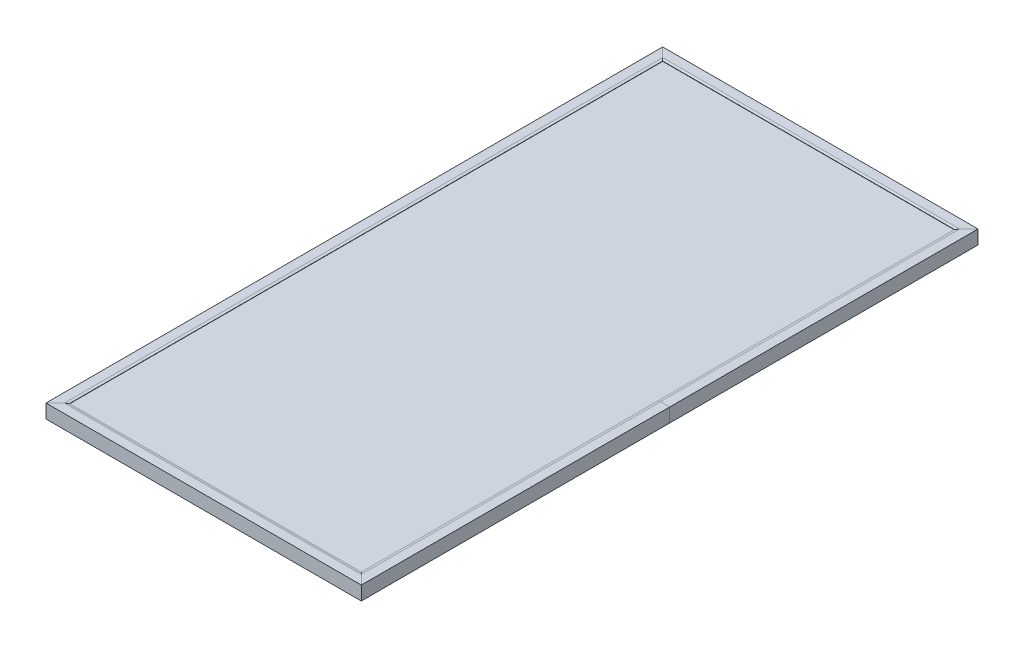
SolidWorks part; units mm, degrees
ref_plane "Front Plane" through (0, 0, 0) normal (0, 0, 1) x (1, 0, 0)
ref_plane "Top Plane" through (0, 0, 0) normal (0, 1, 0) x (1, 0, 0)
ref_plane "Right Plane" through (0, 0, 0) normal (1, 0, 0) x (0, 0, -1)
sketch "Solar Panel Dimensions" plane through (0, 0, 0) normal (0, 1, 0) x (1, 0, 0)
  line L0 (-403.86, 789.94) -> (403.86, 789.94)
  line L1 (-403.86, 789.94) -> (-403.86, -789.94)
  line L2 (403.86, 789.94) -> (403.86, -789.94)
  line L3 (-403.86, -789.94) -> (403.86, -789.94)
  line L4 (-403.86, 789.94) -> (403.86, -789.94) construction
  line L5 (403.86, 789.94) -> (-403.86, -789.94) construction
  point P1 (0, 0)
  dimension "D1" = 1579.88
  dimension "D2" = 807.72
sketch "Bracket" plane through (0, 0, 0) normal (0, 0, 1) x (1, 0, 0)
  line L0 (403.86, 0) -> (373.86, 0)
  line L1 (373.86, 33.56) -> (373.86, 34.2641)
  line L2 (-403.86, 0) -> (403.86, 0) construction
  line L3 (-403.86, 0) -> (403.86, 0) construction
  line L4 (373.86, 0) -> (373.86, 1.2)
  line L5 (373.86, 1.2) -> (399.86, 1.2)
  line L6 (399.86, 1.2) -> (399.86, 33.56)
  line L7 (399.86, 33.56) -> (373.86, 33.56)
  line L8 (373.86, 33.56) -> (373.86, 35.56) construction
  line L9 (373.86, 35.56) -> (403.86, 35.56) construction
  line L10 (403.86, 35.56) -> (403.86, 0)
  line L11 (373.86, 34.2641) -> (380.2941, 35.56)
  line L12 (-403.86, 0) -> (403.86, 0) construction
  line L13 (380.2941, 35.56) -> (403.86, 35.56)
  point P3 (403.86, 0)
  dimension "D1" = 1.2
  dimension "D2" = 2
  dimension "D3" = 4
  dimension "D4" = 35.56
  dimension "D5" = 30
  dimension "D6" = 6.4341
  dimension "D7" = 0.7041
sweep "Sweep1" add profiles "Bracket" path "Solar Panel Dimensions"
sketch "Sketch3" plane through (0, 33.56, 0) normal (0, -1, 0) x (1, 0, 0)
  line L1 (-373.86, 759.94) -> (373.86, 759.94)
  line L2 (-373.86, 759.94) -> (-373.86, -759.94)
  line L3 (-373.86, -759.94) -> (373.86, -759.94)
  line L4 (373.86, 759.94) -> (373.86, -759.94)
extrude "Boss-Extrude1" add sketch "Sketch3" along normal blind 3 separate body
sketch "Sketch4" plane through (0, 30.56, 0) normal (0, -1, 0) x (1, 0, 0)
  line L0 (55, -659.94) -> (-55, -659.94)
  line L1 (-55, -659.94) -> (-55, -584.94)
  line L2 (-55, -584.94) -> (-20, -584.94)
  line L3 (-20, -584.94) -> (-20, -604.94)
  line L4 (-20, -604.94) -> (20, -604.94)
  line L5 (20, -604.94) -> (20, -584.94)
  line L6 (20, -584.94) -> (55, -584.94)
  line L7 (55, -584.94) -> (55, -659.94)
  line L8 (373.86, -759.94) -> (-373.86, -759.94) construction
  line L9 (0, -759.94) -> (0, -659.94) construction
  dimension "D1" = 35
  dimension "D2" = 35
  dimension "D3" = 40
  dimension "D4" = 75
  dimension "D5" = 20
  dimension "D6" = 100
extrude "Boss-Extrude2" add sketch "Sketch4" along normal blind 10
ref_plane "Plane1" through (0, 0, 0) normal (0, -1, 0) x (-1, 0, 0)
sketch "Sketch5" plane through (0, 0, 0) normal (0, -1, 0) x (-1, 0, 0)
  line L0 (-384.36, 651.44) -> (-384.36, 646.44) construction
  line L1 (-379.86, 651.44) -> (-379.86, 646.44)
  line L2 (-388.86, 651.44) -> (-388.86, 646.44)
  line L3 (-403.86, 789.94) -> (-403.86, 0) construction
  line L4 (403.86, 789.94) -> (-403.86, 789.94) construction
  line L5 (-384.36, 401.44) -> (-384.36, 396.44) construction
  line L6 (-379.86, 401.44) -> (-379.86, 396.44)
  line L7 (-388.86, 401.44) -> (-388.86, 396.44)
  line L8 (-384.36, 651.44) -> (-384.36, 609.8863) construction
  line L9 (-384.36, -398.56) -> (-384.36, -403.56) construction
  line L10 (-379.86, -398.56) -> (-379.86, -403.56)
  line L11 (-388.86, -398.56) -> (-388.86, -403.56)
  line L12 (-384.36, -648.56) -> (-384.36, -653.56) construction
  line L13 (-379.86, -648.56) -> (-379.86, -653.56)
  line L14 (-388.86, -648.56) -> (-388.86, -653.56)
  line L15 (-384.36, -398.56) -> (-384.36, 579.3685) construction
  line L16 (0, 881.6947) -> (0, -931.728) construction
  line L17 (384.36, -398.56) -> (384.36, 579.3685) construction
  line L18 (384.36, 651.44) -> (384.36, 609.8863) construction
  line L19 (384.36, -648.56) -> (384.36, -653.56) construction
  line L20 (379.86, -648.56) -> (379.86, -653.56)
  line L21 (388.86, -648.56) -> (388.86, -653.56)
  line L22 (384.36, 401.44) -> (384.36, 396.44) construction
  line L23 (379.86, 401.44) -> (379.86, 396.44)
  line L24 (388.86, 401.44) -> (388.86, 396.44)
  line L25 (384.36, -398.56) -> (384.36, -403.56) construction
  line L26 (379.86, -398.56) -> (379.86, -403.56)
  line L27 (388.86, -398.56) -> (388.86, -403.56)
  line L28 (384.36, 651.44) -> (384.36, 646.44) construction
  line L29 (379.86, 651.44) -> (379.86, 646.44)
  line L30 (388.86, 651.44) -> (388.86, 646.44)
  arc A0 (-379.86, 651.44) -> (-388.86, 651.44) centre (-384.36, 651.44) ccw
  arc A1 (-388.86, 646.44) -> (-379.86, 646.44) centre (-384.36, 646.44) ccw
  arc A2 (-379.86, 401.44) -> (-388.86, 401.44) centre (-384.36, 401.44) ccw
  arc A3 (-388.86, 396.44) -> (-379.86, 396.44) centre (-384.36, 396.44) ccw
  arc A4 (-379.86, -398.56) -> (-388.86, -398.56) centre (-384.36, -398.56) ccw
  arc A5 (-388.86, -403.56) -> (-379.86, -403.56) centre (-384.36, -403.56) ccw
  arc A6 (-379.86, -648.56) -> (-388.86, -648.56) centre (-384.36, -648.56) ccw
  arc A7 (-388.86, -653.56) -> (-379.86, -653.56) centre (-384.36, -653.56) ccw
  arc A8 (379.86, -648.56) -> (388.86, -648.56) centre (384.36, -648.56) cw
  arc A9 (388.86, -653.56) -> (379.86, -653.56) centre (384.36, -653.56) cw
  arc A10 (379.86, 401.44) -> (388.86, 401.44) centre (384.36, 401.44) cw
  arc A11 (388.86, 396.44) -> (379.86, 396.44) centre (384.36, 396.44) cw
  arc A12 (379.86, -398.56) -> (388.86, -398.56) centre (384.36, -398.56) cw
  arc A13 (388.86, -403.56) -> (379.86, -403.56) centre (384.36, -403.56) cw
  arc A14 (379.86, 651.44) -> (388.86, 651.44) centre (384.36, 651.44) cw
  arc A15 (388.86, 646.44) -> (379.86, 646.44) centre (384.36, 646.44) cw
  point P2 (-384.36, 648.94)
  point P10 (-384.36, 641.94)
  point P12 (-384.36, 655.94)
  point P15 (-384.36, -401.06)
  point P18 (-384.36, 398.94)
  point P23 (-384.36, 391.94)
  point P24 (-384.36, 663.1984)
  point P26 (-384.36, 405.94)
  point P27 (-422.1737, 679.0016)
  point P28 (-379.86, 398.94)
  point P34 (-384.36, -408.06)
  point P35 (-384.36, -394.06)
  point P38 (-384.36, -651.06)
  point P43 (-384.36, -658.06)
  point P44 (-732.6396, 632.6806)
  point P45 (-384.36, -644.06)
  point P46 (-379.86, -651.06)
  point P56 (384.36, -644.06)
  point P59 (384.36, -651.06)
  point P64 (384.36, -394.06)
  point P65 (422.1737, 679.0016)
  point P66 (384.36, 405.94)
  point P67 (384.36, 663.1984)
  point P70 (384.36, 398.94)
  point P76 (384.36, -401.06)
  point P81 (384.36, 655.94)
  point P83 (384.36, 648.94)
  dimension "D1" = 15
  dimension "D2" = 9
  dimension "D3" = 14
  dimension "D4" = 134
  dimension "D5" = 9
  dimension "D6" = 14
  dimension "D7" = 250
  dimension "D8" = 14
  dimension "D9" = 9
  dimension "D10" = 14
  dimension "D11" = 250
  dimension "D12" = 9
  dimension "D13" = 800
extrude "Cut-Extrude1" cut sketch "Sketch5" against normal up to next (1.2 mm away)
sketch "Sketch6" plane through (0, 0, 0) normal (0, -1, 0) x (-1, 0, 0)
  line L0 (0, 908.8724) -> (0, -1241.4517)
  line L1 (-610.4688, 0) -> (890.7295, 0)
sketch "Sketch7" plane through (0, 0, 0) normal (0, -1, 0) x (-1, 0, 0)
  line L0 (379.86, 398.94) -> (388.86, 398.94)
  line L1 (379.86, 401.44) -> (379.86, 396.44) construction
  line L2 (388.86, 396.44) -> (388.86, 401.44) construction
  line L3 (384.36, 405.94) -> (384.36, 391.94)
  line L4 (384.36, -394.06) -> (384.36, -408.06)
  line L5 (379.86, -401.06) -> (388.86, -401.06)
  line L6 (379.86, -398.56) -> (379.86, -403.56) construction
  line L7 (388.86, -403.56) -> (388.86, -398.56) construction
  line L8 (-384.36, 405.94) -> (-384.36, 391.94)
  line L9 (-379.86, 398.94) -> (-388.86, 398.94)
  line L10 (-379.86, 396.44) -> (-379.86, 401.44) construction
  line L11 (-388.86, 401.44) -> (-388.86, 396.44) construction
  arc A0 (388.86, 401.44) -> (379.86, 401.44) centre (384.36, 401.44) ccw construction
  arc A1 (379.86, 396.44) -> (388.86, 396.44) centre (384.36, 396.44) ccw construction
  arc A2 (388.86, -398.56) -> (379.86, -398.56) centre (384.36, -398.56) ccw construction
  arc A3 (379.86, -403.56) -> (388.86, -403.56) centre (384.36, -403.56) ccw construction
  arc A4 (-379.86, 401.44) -> (-388.86, 401.44) centre (-384.36, 401.44) ccw construction
  arc A5 (-388.86, 396.44) -> (-379.86, 396.44) centre (-384.36, 396.44) ccw construction
  point P42 (384.36, 398.94)
  point P43 (-384.36, 398.94)
  point P44 (384.36, -401.06)
sketch "Sketch8" plane through (0, 0, 0) normal (0, -1, 0) x (1, 0, 0)
  line L0 (-384.36, 408.06) -> (-384.36, -405.94) construction
  line L1 (610.4688, 0) -> (-890.7295, 0) construction
  line L2 (0, 759.94) -> (0, -789.94) construction
  line L3 (373.86, 759.94) -> (-373.86, 759.94) construction
  line L4 (-403.86, -789.94) -> (403.86, -789.94) construction
  circle A0 centre (-384.36, 228.6) radius 4.5
  circle A1 centre (-384.36, -228.6) radius 4.5
  circle A2 centre (384.36, 228.6) radius 4.5
  circle A3 centre (384.36, -228.6) radius 4.5
  dimension "D3" = 9
  dimension "D4" = 9
  dimension "D1" = 228.6
  dimension "D2" = 228.6
extrude "extra cut hole for side panel mount" cut sketch "Sketch8" against normal up to next (1.2 mm away)
sketch "Sketch9" plane through (0, 0, 0) normal (0, -1, 0) x (1, 0, 0)
  point P0 (-384.36, 228.6)
  point P1 (-384.36, -228.6)
  point P3 (384.36, 228.6)
  point P5 (384.36, -228.6)
equation "\"panelthickness\"= 1.4in"
equation "\"D4@Bracket\" = \"panelthickness\""
equation "\"PanelHeight\"=1579.88"
equation "\"D1@Solar Panel Dimensions\"=\"PanelHeight\""
equation "\"PanelWidth\"=807.72"
equation "\"D2@Solar Panel Dimensions\"=\"PanelWidth\""
